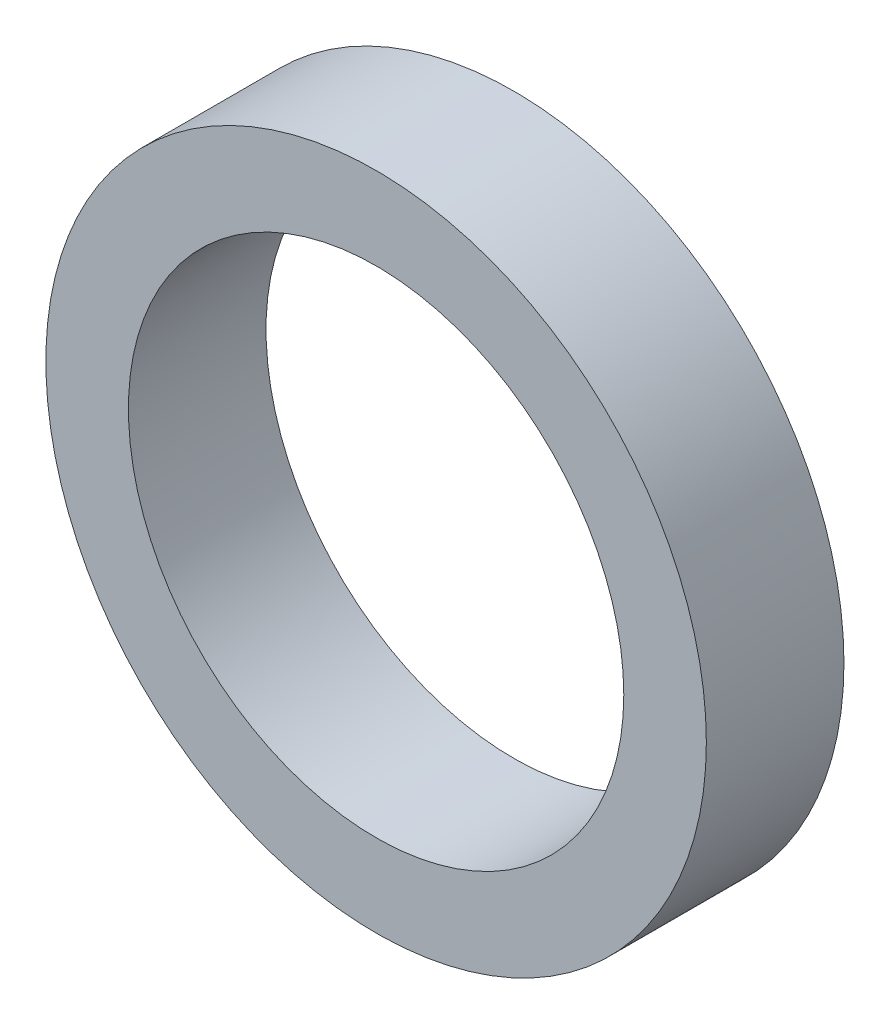
SolidWorks part; units mm, degrees
ref_plane "Front Plane" through (0, 0, 0) normal (0, 0, 1) x (1, 0, 0)
ref_plane "Top Plane" through (0, 0, 0) normal (0, 1, 0) x (1, 0, 0)
ref_plane "Right Plane" through (0, 0, 0) normal (1, 0, 0) x (0, 0, -1)
sketch "Sketch1" plane through (0, 0, 0) normal (0, 0, 1) x (1, 0, 0)
  circle A0 centre (0, 0) radius 9
  circle A1 centre (0, 0) radius 12
  dimension "D1" = 18
  dimension "D2" = 24
extrude "Boss-Extrude1" add sketch "Sketch1" along normal blind 5 contours A1
